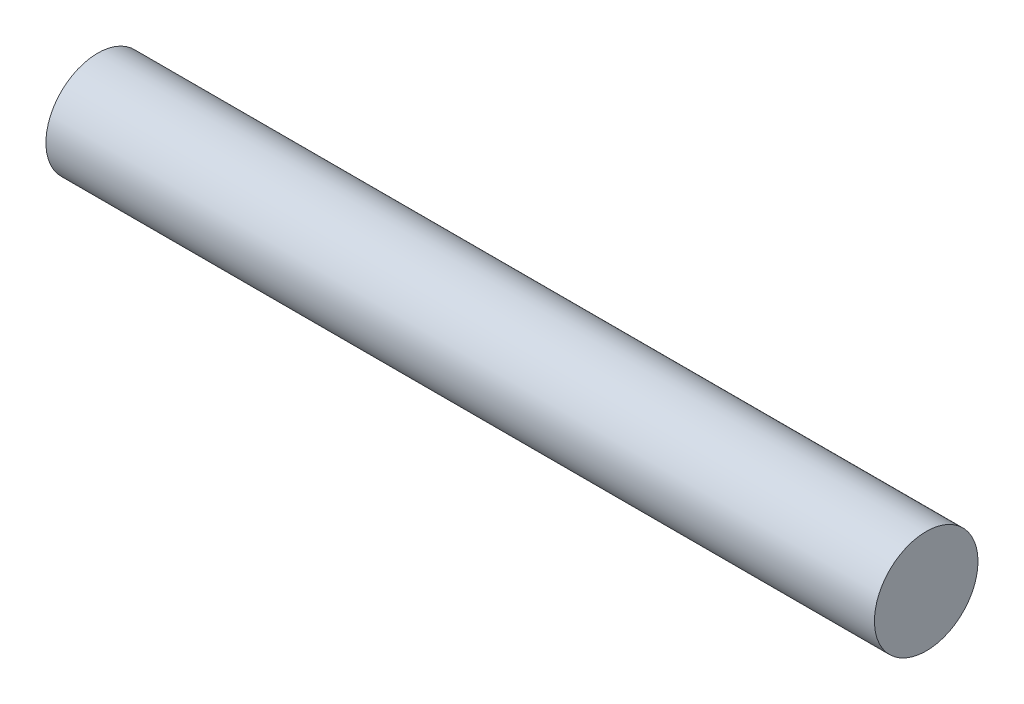
SolidWorks part; units mm, degrees
ref_plane "Front Plane" through (0, 0, 0) normal (0, 0, 1) x (1, 0, 0)
ref_plane "Top Plane" through (0, 0, 0) normal (0, 1, 0) x (1, 0, 0)
ref_plane "Right Plane" through (0, 0, 0) normal (1, 0, 0) x (0, 0, -1)
sketch "Sketch1" plane through (0, 0, 0) normal (1, 0, 0) x (0, 0, -1)
  circle A0 centre (0, 0) radius 1
  dimension "D1" = 2
extrude "Boss-Extrude1" add sketch "Sketch1" along normal blind 16
ref_plane "Plane2" through (8, 0, 0) normal (1, 0, 0) x (0, 0, -1)
